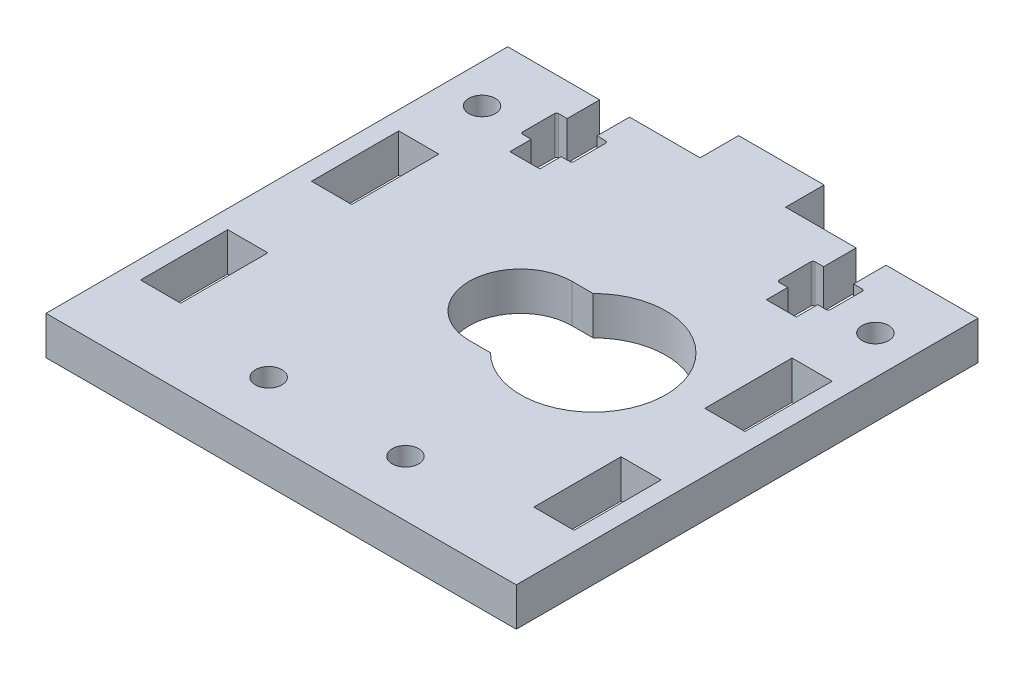
SolidWorks part; units mm, degrees
ref_plane "Front Plane" through (0, 0, 0) normal (0, 0, 1) x (1, 0, 0)
ref_plane "Top Plane" through (0, 0, 0) normal (0, 1, 0) x (1, 0, 0)
ref_plane "Right Plane" through (0, 0, 0) normal (1, 0, 0) x (0, 0, -1)
sketch "Sketch1" plane through (0, 0, 0) normal (0, 1, 0) x (1, 0, 0)
  line L1 (-27.5, 27) -> (27.5, 27)
  line L2 (-27.5, 27) -> (-27.5, -27)
  line L3 (-27.5, -27) -> (27.5, -27)
  line L4 (27.5, 27) -> (27.5, -27)
  line L5 (-27.5, 27) -> (27.5, -27) construction
  line L6 (-27.5, -27) -> (27.5, 27) construction
  point P0 (0, 0)
  dimension "D1" = 55
  dimension "D2" = 54
extrude "MainShape" add sketch "Sketch1" along normal blind 4.5
sketch "Sketch2" plane through (0, 4.5, 0) normal (0, 1, 0) x (1, 0, 0)
  line L0 (0, -27) -> (0, 27) construction
  line L1 (-27.5, -27) -> (27.5, -27) construction
  line L2 (27.5, 27) -> (-27.5, 27) construction
  line L4 (-5, 31.5) -> (5, 31.5)
  line L5 (-5, 31.5) -> (-5, 22.5)
  line L6 (-5, 22.5) -> (5, 22.5)
  line L7 (5, 31.5) -> (5, 22.5)
  line L8 (-5, 31.5) -> (5, 22.5) construction
  line L9 (-5, 22.5) -> (5, 31.5) construction
  dimension "D1" = 10
  dimension "D2" = 4.5
extrude "Tab1" add sketch "Sketch2" against normal through all
sketch "Sketch4" plane through (0, 4.5, 0) normal (0, 1, 0) x (1, 0, 0)
  line L0 (0, 31.5) -> (0, -27) construction
  line L1 (5, 31.5) -> (-5, 31.5) construction
  line L2 (-27.5, -27) -> (27.5, -27) construction
  line L3 (-15, 27) -> (-15, 16.5) construction
  line L4 (-5, 27) -> (-27.5, 27) construction
  line L5 (-13.25, 16.5) -> (-16.75, 16.5) construction
  line L6 (-16.75, 16.5) -> (-16.75, 27) construction
  line L7 (-13.25, 16.5) -> (-16.75, 16.5)
  line L8 (-16.75, 16.5) -> (-16.75, 19)
  line L9 (-16.75, 19) -> (-17.75, 19)
  line L10 (-18, 19.25) -> (-18, 22.95)
  line L11 (-17.75, 23.2) -> (-16.75, 23.2)
  line L12 (-16.75, 23.2) -> (-16.75, 27)
  line L13 (-16.75, 27) -> (-13.25, 27)
  line L14 (-13.25, 16.5) -> (-13.25, 27) construction
  line L15 (-13.25, 23.2) -> (-13.25, 27)
  line L16 (-12.25, 23.2) -> (-13.25, 23.2)
  line L17 (-12, 19.25) -> (-12, 22.95)
  line L18 (-13.25, 19) -> (-12.25, 19)
  line L19 (-13.25, 16.5) -> (-13.25, 19)
  line L20 (13.25, 16.5) -> (13.25, 27) construction
  line L21 (16.75, 16.5) -> (16.75, 27) construction
  line L22 (13.25, 16.5) -> (16.75, 16.5) construction
  line L23 (15, 27) -> (15, 16.5) construction
  line L24 (13.25, 16.5) -> (13.25, 19)
  line L25 (13.25, 19) -> (12.25, 19)
  line L26 (12, 19.25) -> (12, 22.95)
  line L27 (12.25, 23.2) -> (13.25, 23.2)
  line L28 (13.25, 23.2) -> (13.25, 27)
  line L29 (16.75, 27) -> (13.25, 27)
  line L30 (16.75, 23.2) -> (16.75, 27)
  line L31 (17.75, 23.2) -> (16.75, 23.2)
  line L32 (18, 19.25) -> (18, 22.95)
  line L33 (16.75, 19) -> (17.75, 19)
  line L34 (16.75, 16.5) -> (16.75, 19)
  line L35 (13.25, 16.5) -> (16.75, 16.5)
  arc A0 (-17.75, 19) -> (-18, 19.25) centre (-17.75, 19.25) cw
  arc A1 (-12, 19.25) -> (-12.25, 19) centre (-12.25, 19.25) cw
  arc A2 (-12.25, 23.2) -> (-12, 22.95) centre (-12.25, 22.95) cw
  arc A3 (-18, 22.95) -> (-17.75, 23.2) centre (-17.75, 22.95) cw
  arc A4 (18, 22.95) -> (17.75, 23.2) centre (17.75, 22.95) ccw
  arc A5 (12.25, 23.2) -> (12, 22.95) centre (12.25, 22.95) ccw
  arc A6 (12, 19.25) -> (12.25, 19) centre (12.25, 19.25) ccw
  arc A7 (17.75, 19) -> (18, 19.25) centre (17.75, 19.25) ccw
  point P24 (-18, 19)
  point P27 (-12, 19)
  point P30 (-12, 23.2)
  point P33 (-18, 23.2)
  point P56 (18, 23.2)
  point P57 (12, 23.2)
  point P58 (12, 19)
  point P59 (18, 19)
  dimension "D7" = 0.25
  dimension "D1" = 10.5
  dimension "D2" = 1.75
  dimension "D3" = 4.2
  dimension "D4" = 3
  dimension "D5" = 8
  dimension "D6" = 15
extrude "Cut-Extrude2" cut sketch "Sketch4" against normal through all
sketch "Sketch5" plane through (0, 4.5, 0) normal (0, 1, 0) x (1, 0, 0)
  line L0 (0, -27) -> (0, 31.5) construction
  line L1 (-27.5, -27) -> (27.5, -27) construction
  line L2 (5, 31.5) -> (-5, 31.5) construction
  line L3 (23, 27) -> (23, -27) construction
  line L4 (27.5, 27) -> (16.75, 27) construction
  line L5 (-23, 27) -> (-23, -27) construction
  line L6 (20.65, 12.1) -> (25.35, 12.1)
  line L7 (20.65, 12.1) -> (20.65, 1.9)
  line L8 (20.65, 1.9) -> (25.35, 1.9)
  line L9 (25.35, 12.1) -> (25.35, 1.9)
  line L10 (20.65, 12.1) -> (25.35, 1.9) construction
  line L11 (20.65, 1.9) -> (25.35, 12.1) construction
  line L12 (-20.65, 1.9) -> (-25.35, 12.1) construction
  line L13 (-20.65, 12.1) -> (-25.35, 1.9) construction
  line L14 (-25.35, 12.1) -> (-25.35, 1.9)
  line L15 (-20.65, 1.9) -> (-25.35, 1.9)
  line L16 (-20.65, 12.1) -> (-20.65, 1.9)
  line L17 (-20.65, 12.1) -> (-25.35, 12.1)
  line L18 (-27.5, -3) -> (27.5, -3) construction
  line L19 (-27.5, 27) -> (-27.5, -27) construction
  line L20 (27.5, -27) -> (27.5, 27) construction
  line L21 (-20.65, -18.1) -> (-25.35, -7.9) construction
  line L22 (-20.65, -7.9) -> (-25.35, -18.1) construction
  line L23 (20.65, -7.9) -> (25.35, -18.1) construction
  line L24 (20.65, -18.1) -> (25.35, -7.9) construction
  line L25 (-20.65, -18.1) -> (-25.35, -18.1)
  line L26 (-20.65, -18.1) -> (-20.65, -7.9)
  line L27 (-20.65, -7.9) -> (-25.35, -7.9)
  line L28 (-25.35, -18.1) -> (-25.35, -7.9)
  line L29 (25.35, -18.1) -> (25.35, -7.9)
  line L30 (20.65, -7.9) -> (25.35, -7.9)
  line L31 (20.65, -18.1) -> (20.65, -7.9)
  line L32 (20.65, -18.1) -> (25.35, -18.1)
  line L33 (-20.65, 12.1) -> (-25.35, 1.9) construction
  point P10 (23, 7)
  point P21 (-23, 7)
  point P36 (-23, -13)
  point P37 (23, -13)
  dimension "D1" = 23
  dimension "D2" = 10.2
  dimension "D3" = 4.7
  dimension "D4" = 20
  dimension "D5" = 20
extrude "Cut-Extrude3" cut sketch "Sketch5" against normal through all
sketch "Sketch6" plane through (0, 4.5, 0) normal (0, 1, 0) x (1, 0, 0)
  line L0 (0, -27) -> (0, 27) construction
  line L1 (5, 31.5) -> (-5, 31.5) construction
  line L3 (-27.5, 1) -> (27.5, 1) construction
  line L4 (-27.5, 27) -> (-27.5, -27) construction
  line L5 (27.5, -27) -> (27.5, 27) construction
  line L6 (27.5, 27) -> (16.75, 27) construction
  line L7 (-27.5, -27) -> (27.5, -27) construction
  line L9 (-27.5, 27) -> (27.5, 27) construction
  circle A0 centre (0, 1) radius 12
  point P4 (0, 31.5)
  dimension "D1" = 24
  dimension "D2" = 26
extrude "Cut-Extrude4" cut sketch "Sketch6" against normal through all
sketch "Sketch7" plane through (0, 4.5, 0) normal (0, 1, 0) x (1, 0, 0)
  line L0 (0, 1) -> (0, -27) construction
  line L3 (-27.5, -27) -> (27.5, -27) construction
  line L4 (8, -20.46) -> (-8, -20.46) construction
  circle A1 centre (-8, -20.46) radius 1.55
  circle A2 centre (8, -20.46) radius 1.55
  point P8 (0, -20.46)
  dimension "D1" = 3.1
  dimension "D2" = 8
  dimension "D3" = 21.46
extrude "Cut-Extrude5" [suppressed] cut sketch "Sketch7" against normal through all
sketch "Sketch8" plane through (0, 4.5, 0) normal (0, 1, 0) x (1, 0, 0)
  line L0 (-12, 1) -> (12, 1) construction
  line L1 (0, 1) -> (0, -20.46) construction
  line L2 (8, -20.46) -> (-8, -20.46) construction
  line L3 (0, -11) -> (0, 13) construction
  circle A0 centre (-8, -20.46) radius 1.55
  circle A1 centre (0, 1) radius 12 construction
  circle A2 centre (8, -20.46) radius 1.55
  dimension "D2" = 8
  dimension "D3" = 3.1
  dimension "D1" = 90
  dimension "D4" = 21.46
extrude "Cut-Extrude6" cut sketch "Sketch8" against normal through all
sketch "Sketch9" plane through (0, 4.5, 0) normal (0, 1, 0) x (1, 0, 0)
  line L0 (0, -27) -> (0, 31.5) construction
  line L1 (-27.5, -27) -> (27.5, -27) construction
  line L2 (5, 31.5) -> (-5, 31.5) construction
  line L3 (16, -27) -> (16, -16.5) construction
  line L4 (14.25, -16.5) -> (17.75, -16.5) construction
  line L5 (17.75, -16.5) -> (17.75, -27) construction
  line L6 (17.75, -27) -> (17.75, -23.2)
  line L7 (17.75, -23.2) -> (18.75, -23.2)
  line L8 (19, -22.95) -> (19, -19.25)
  line L9 (18.75, -19) -> (17.75, -19)
  line L10 (17.75, -19) -> (17.75, -16.5)
  line L11 (17.75, -16.5) -> (14.25, -16.5)
  line L12 (17.75, -27) -> (14.25, -27)
  line L13 (14.25, -16.5) -> (14.25, -27) construction
  line L14 (14.25, -19) -> (14.25, -16.5)
  line L15 (13.25, -19) -> (14.25, -19)
  line L16 (13, -22.95) -> (13, -19.25)
  line L17 (14.25, -23.2) -> (13.25, -23.2)
  line L18 (14.25, -27) -> (14.25, -23.2)
  line L19 (-14.25, -16.5) -> (-14.25, -27) construction
  line L20 (-17.75, -16.5) -> (-17.75, -27) construction
  line L21 (-14.25, -16.5) -> (-17.75, -16.5) construction
  line L22 (-16, -27) -> (-16, -16.5) construction
  line L23 (-14.25, -27) -> (-14.25, -23.2)
  line L24 (-14.25, -23.2) -> (-13.25, -23.2)
  line L25 (-13, -22.95) -> (-13, -19.25)
  line L26 (-13.25, -19) -> (-14.25, -19)
  line L27 (-14.25, -19) -> (-14.25, -16.5)
  line L28 (-17.75, -27) -> (-14.25, -27)
  line L29 (-17.75, -16.5) -> (-14.25, -16.5)
  line L30 (-17.75, -19) -> (-17.75, -16.5)
  line L31 (-18.75, -19) -> (-17.75, -19)
  line L32 (-19, -22.95) -> (-19, -19.25)
  line L33 (-17.75, -23.2) -> (-18.75, -23.2)
  line L34 (-17.75, -27) -> (-17.75, -23.2)
  arc A0 (18.75, -23.2) -> (19, -22.95) centre (18.75, -22.95) ccw
  arc A1 (19, -19.25) -> (18.75, -19) centre (18.75, -19.25) ccw
  arc A2 (13, -19.25) -> (13.25, -19) centre (13.25, -19.25) cw
  arc A3 (13.25, -23.2) -> (13, -22.95) centre (13.25, -22.95) cw
  arc A4 (-13.25, -23.2) -> (-13, -22.95) centre (-13.25, -22.95) ccw
  arc A5 (-13, -19.25) -> (-13.25, -19) centre (-13.25, -19.25) ccw
  arc A6 (-19, -19.25) -> (-18.75, -19) centre (-18.75, -19.25) cw
  arc A7 (-18.75, -23.2) -> (-19, -22.95) centre (-18.75, -22.95) cw
  point P16 (19, -23.2)
  point P19 (19, -19)
  point P30 (13, -19)
  point P31 (13, -23.2)
  point P54 (-13, -23.2)
  point P55 (-13, -19)
  point P56 (-19, -19)
  point P57 (-19, -23.2)
  dimension "D7" = 0.25
  dimension "D1" = 10.5
  dimension "D2" = 1.75
  dimension "D3" = 8
  dimension "D4" = 4.2
  dimension "D5" = 3
  dimension "D6" = 16
extrude "Cut-Extrude7" [suppressed] cut sketch "Sketch9" against normal through all
sketch "Sketch10" [suppressed] plane through (0, 0, 27) normal (0, 0, 1) x (1, 0, 0)
  line L0 (-27.5, 2.25) -> (27.5, 2.25) construction
  line L1 (-27.5, 4.5) -> (-27.5, 0) construction
  line L2 (27.5, 4.5) -> (27.5, 0) construction
  line L3 (-16, 4.5) -> (-16, 0) construction
  line L4 (-14.25, 4.5) -> (-17.75, 4.5) construction
  line L5 (16, 4.5) -> (16, 0) construction
  line L6 (17.75, 4.5) -> (14.25, 4.5) construction
  line L7 (17.75, 0) -> (14.25, 0) construction
  line L8 (-14.25, 0) -> (-17.75, 0) construction
  circle A0 centre (-16, 2.25) radius 1.6
  circle A1 centre (16, 2.25) radius 1.6
  dimension "D1" = 3.2
  dimension "D2" = 3.2
sketch "Sketch11" plane through (0, 4.5, 0) normal (0, 1, 0) x (1, 0, 0)
  line L0 (-20.65, 7) -> (-25.35, 7) construction
  line L1 (-20.65, 1.9) -> (-20.65, 12.1) construction
  line L2 (-25.35, 12.1) -> (-25.35, 1.9) construction
  line L3 (-23, 7) -> (-23, 27) construction
  line L4 (-16.75, 27) -> (-27.5, 27) construction
  line L5 (0, 31.5) -> (0, 0) construction
  line L6 (5, 31.5) -> (-5, 31.5) construction
  line L7 (23, 7) -> (23, 27) construction
  line L8 (20.65, 7) -> (25.35, 7) construction
  line L9 (-23, 7) -> (-23, 27) construction
  circle A0 centre (-23, 19.5) radius 1.55
  circle A1 centre (23, 19.5) radius 1.55
  dimension "D1" = 3.1
  dimension "D2" = 7.5
extrude "Cut-Extrude8" cut sketch "Sketch11" against normal through all
sketch "Sketch12" [suppressed] plane through (0, 4.5, 0) normal (0, 1, 0) x (1, 0, 0)
  line L0 (-27.5, -7) -> (-34, -17)
  line L1 (-27.5, 27) -> (-27.5, -27) construction
  line L2 (-34, -17) -> (-34, -27)
  line L3 (-34, -27) -> (-27.5, -27)
  line L4 (-27.5, -27) -> (-27.5, -7)
  line L5 (-27.5, -27) -> (27.5, -27) construction
  line L6 (0, -27) -> (0, 31.5) construction
  line L7 (5, 31.5) -> (-5, 31.5) construction
  line L8 (27.5, -27) -> (27.5, -7)
  line L9 (34, -27) -> (27.5, -27)
  line L10 (34, -17) -> (34, -27)
  line L11 (27.5, -7) -> (34, -17)
  point P4 (0, -27)
  dimension "D1" = 34
  dimension "D2" = 10
  dimension "D3" = 20
extrude "Boss-Extrude1" [suppressed] add sketch "Sketch12" against normal through all
sketch "Sketch14" [suppressed] plane through (0, 4.5, 0) normal (0, 1, 0) x (1, 0, 0)
  line L0 (-34, -27) -> (34, -27) construction
  line L2 (-34, -27) -> (34, -27) construction
  line L3 (0, -27) -> (0, 31.5) construction
  line L4 (5, 31.5) -> (-5, 31.5) construction
  line L6 (26.25, -16.5) -> (26.25, -27) construction
  line L8 (-28, -27) -> (-28, -16.5) construction
  line L9 (-26.25, -16.5) -> (-29.75, -16.5) construction
  line L10 (-29.75, -16.5) -> (-29.75, -27) construction
  line L11 (-26.25, -27) -> (-29.75, -27)
  line L12 (-29.75, -27) -> (-29.75, -23.2)
  line L13 (-29.75, -23.2) -> (-30.75, -23.2)
  line L14 (-31, -22.95) -> (-31, -19.25)
  line L15 (-30.75, -19) -> (-29.75, -19)
  line L16 (-29.75, -19) -> (-29.75, -16.5)
  line L17 (-29.75, -16.5) -> (-26.25, -16.5)
  line L18 (-26.25, -16.5) -> (-26.25, -27) construction
  line L19 (-26.25, -19) -> (-26.25, -16.5)
  line L20 (-25.25, -19) -> (-26.25, -19)
  line L21 (-25, -22.95) -> (-25, -19.25)
  line L22 (-26.25, -23.2) -> (-25.25, -23.2)
  line L23 (-26.25, -27) -> (-26.25, -23.2)
  line L24 (29.75, -16.5) -> (29.75, -27) construction
  line L25 (26.25, -16.5) -> (29.75, -16.5) construction
  line L26 (28, -27) -> (28, -16.5) construction
  line L27 (26.25, -27) -> (26.25, -23.2)
  line L28 (26.25, -23.2) -> (25.25, -23.2)
  line L29 (25, -22.95) -> (25, -19.25)
  line L30 (25.25, -19) -> (26.25, -19)
  line L31 (26.25, -19) -> (26.25, -16.5)
  line L32 (29.75, -16.5) -> (26.25, -16.5)
  line L33 (29.75, -19) -> (29.75, -16.5)
  line L34 (30.75, -19) -> (29.75, -19)
  line L35 (31, -22.95) -> (31, -19.25)
  line L36 (29.75, -23.2) -> (30.75, -23.2)
  line L37 (29.75, -27) -> (29.75, -23.2)
  line L38 (26.25, -27) -> (29.75, -27)
  line L39 (-26.25, -16.5) -> (-26.25, -27) construction
  arc A0 (-30.75, -23.2) -> (-31, -22.95) centre (-30.75, -22.95) cw
  arc A1 (-31, -19.25) -> (-30.75, -19) centre (-30.75, -19.25) cw
  arc A2 (-25, -19.25) -> (-25.25, -19) centre (-25.25, -19.25) ccw
  arc A3 (-25.25, -23.2) -> (-25, -22.95) centre (-25.25, -22.95) ccw
  arc A4 (25.25, -23.2) -> (25, -22.95) centre (25.25, -22.95) cw
  arc A5 (25, -19.25) -> (25.25, -19) centre (25.25, -19.25) cw
  arc A6 (31, -19.25) -> (30.75, -19) centre (30.75, -19.25) ccw
  arc A7 (30.75, -23.2) -> (31, -22.95) centre (30.75, -22.95) ccw
  point P2 (0, -27)
  dimension "D10" = 0.25
  dimension "D4" = 1.75
  dimension "D6" = 10.5
  dimension "D2" = 28
  dimension "D3" = 3
  dimension "D5" = 4.2
  dimension "D7" = 8
extrude "Cut-Extrude9" [suppressed] cut sketch "Sketch14" against normal through all
sketch "Sketch15" plane through (0, 4.5, 0) normal (0, 1, 0) x (1, 0, 0)
  circle A0 centre (0, 1) radius 12
  circle A1 centre (0, 1) radius 6
  circle A2 centre (0, 1) radius 12 construction
  dimension "D1" = 12
extrude "Boss-Extrude2" add sketch "Sketch15" against normal through all
sketch "Sketch16" plane through (0, 4.5, 0) normal (0, 1, 0) x (1, 0, 0)
  line L0 (0, 1) -> (27.5, 1) construction
  line L1 (27.5, -27) -> (27.5, 27) construction
  line L2 (0, 7) -> (2.4792, 7)
  line L3 (0, -5) -> (2.4792, -5)
  line L4 (0, 7) -> (0, -5)
  arc A0 (2.4792, -5) -> (2.4792, 7) centre (8.5, 1) ccw
  circle A1 centre (0, 1) radius 6 construction
  dimension "D1" = 17
  dimension "D2" = 8.5
extrude "Cut-Extrude10" cut sketch "Sketch16" against normal through all
equation "\"X-ROD-SPACING\"=45"
equation "\"Y-ROD-SPACING\"=75"
equation "\"Z-ROD-SPACING\"=17.5"
equation "\"Y-BED-OFFSET\"=2"
equation "\"Y-BED-ROD-INSET\"=3.5"
equation "\"Y-BED-SCREW-SPACING\"=209"
equation "\"Y-BED-SCREW-CUTOUT-SLOT-HEIGHT\"=2"
equation "\"T-SLOT-NUT-FILLET-RADIUS\"=0.25"
equation "\"T-SLOT-SCREW-SHAFT-RADIUS\"=1.75"
equation "\"T-SLOT-SCREW-SHAFT-CUTOUT-LENGTH\"=10.5"
equation "\"T-SLOT-NUT-DEPTH\"=4.2"
equation "\"T-SLOT-NUT-WIDTH\"=3"
equation "\"T-SLOT-NUT-END-DISTANCE\"=8"
equation "\"ACRYLIC-THICKNESS\"=10"
equation "\"ACRYLIC-THICKNESS2\"=4.5"
equation "\"ACRYLIC-TAB-CUTOUT-SIZE\"=\"ACRYLIC-THICKNESS\"+\"ACRYLIC-TAB-TOLERANCE\"*2"
equation "\"ACRYLIC-TAB-WIDTH\"=\"ACRYLIC-THICKNESS\""
equation "\"ACRYLIC-M3-HOLE\"=3.1"
equation "\"SMOOTHROD-CAP-SCREW-DISTANCE\"=20"
equation "\"FRAME-WIDTH-INNER\"=370"
equation "\"NEMA17-HOLE-SPACING\"=31"
equation "\"NEMA17-CENTRAL-CUTOUT\"=22.5"
equation "\"Z-BRACKET-REACH\"=55"
equation "\"Z-ROD-INSET\"=16"
equation "\"TOP-BRACKET-SPACING\"=40"
equation "\"SMOOTHROD-X-LENGTH\"=350"
equation "\"SMOOTHROD-Y-LENGTH\"=350"
equation "\"SMOOTHROD-Z-LENGTH\"=350"
equation "\"SMOOTHROD-TIGHTENING-HEADROOM\"=.25"
equation "\"LEADSCREW-Z-LENGTH\"=300"
equation "\"SCREW-LENGTH-FRAME\"=\"ACRYLIC-THICKNESS\" + 10"
equation "\"SCREW-LENGTH-MOTOR\"=\"ACRYLIC-THICKNESS\" + 5"
equation "\"SCREW-LENGTH-EXTRUDER\"=28"
equation "\"SCREW-HEAD-RADIUS\"=6"
equation "\"PRINTED-X-SMOOTHROD-DIAMETER\"=8.2"
equation "\"PRINTED-X-SMOOTHROD-CUTOUT\"=10"
equation "\"PRINTED-X-BASE-HEIGHT\"=10"
equation "\"PRINTED-LM8UU-CUTOUT-SIZE\"=15.25"
equation "\"PRINTED-LM8UU-CUTOUT-LENGTH\"=24.5"
equation "\"PRINTED-X-IDLER-HEIGHT\"=16"
equation "\"PSU-MOUNTING-WIDTH\"=95"
equation "\"PSU-MOUNTING-HEIGHT\"=177"
equation "\"Y-BELT-TO-ROD-DISTANCE\"=20"
equation "\"SPOOL-HOLDER-ROD-SPACING\"=150"
equation "\"ACRYLIC-X-CARRIAGE-WIDTH\"=55"
equation "\"ACRYLIC-X-CARRIAGE-HEIGHT\"=75"
equation "\"ACRYLIC-X-CARRIAGE-SCREW-SPACING-X\"=15"
equation "\"ACRYLIC-X-CARRIAGE-SCREW-SPACING-Y\"=33"
equation "\"ACRYLIC-X-CARRIAGE-CENTER-TAB-SPACING\"=14"
equation "\"D1@Sketch1\"=\"ACRYLIC-X-CARRIAGE-WIDTH\""
equation "\"D1@MainShape\" = \"ACRYLIC-THICKNESS2\""
equation "\"D1@Sketch2\"=\"ACRYLIC-TAB-WIDTH\""
equation "\"D2@Sketch2\"=\"ACRYLIC-THICKNESS2\""
equation "\"D1@Sketch4\"=\"T-SLOT-SCREW-SHAFT-CUTOUT-LENGTH\""
equation "\"D2@Sketch4\"=\"T-SLOT-SCREW-SHAFT-RADIUS\""
equation "\"D3@Sketch4\"=\"T-SLOT-NUT-DEPTH\""
equation "\"D4@Sketch4\"=\"T-SLOT-NUT-WIDTH\""
equation "\"D5@Sketch4\"=\"T-SLOT-NUT-END-DISTANCE\""
equation "\"D6@Sketch4\"=\"ACRYLIC-X-CARRIAGE-SCREW-SPACING-X\""
equation "\"D7@Sketch4\"=\"T-SLOT-NUT-FILLET-RADIUS\""
equation "\"ACRYLIC-X-CARRIAGE-EXTRUDER-SHELF-DEPTH\"=\"ACRYLIC-X-CARRIAGE-EXTRUDER-OFFSET\" + 28"
equation "\"D2@Sketch1\"=\"ACRYLIC-X-CARRIAGE-EXTRUDER-SHELF-DEPTH\""
equation "\"ACRYLIC-X-CARRIAGE-LM8UU-CUTOUT-WIDTH\"=24.25"
equation "\"ACRYLIC-X-CARRIAGE-EXTRUDER-BRACE-SPACING\"=23"
equation "\"ACRYLIC-X-CARRIAGE-EXTRUDER-BRACE-TAB-OFFSET\"=20"
equation "\"ACRYLIC-X-CARRIAGE-EXTRUDER-BRACE-HEIGHT\"=35"
equation "\"ACRYLIC-X-CARRIAGE-EXTRUDER-BRACE-SCREW-SPACING\"=22"
equation "\"D1@Sketch5\"=\"ACRYLIC-X-CARRIAGE-EXTRUDER-BRACE-SPACING\""
equation "\"D2@Sketch5\"=\"ACRYLIC-TAB-CUTOUT-SIZE\""
equation "\"D3@Sketch5\"=\"ACRYLIC-THICKNESS2\"+\"ACRYLIC-TAB-TOLERANCE\"*2"
equation "\"D4@Sketch5\"=\"ACRYLIC-X-CARRIAGE-EXTRUDER-BRACE-TAB-OFFSET\""
equation "\"D1@Sketch7\"=\"ACRYLIC-M3-HOLE\""
equation "\"D3@Sketch8\"=\"ACRYLIC-M3-HOLE\""
equation "\"ACRYLIC-X-CARRIAGE-EXTRUDER-ANGLE\"=90"
equation "\"D1@Sketch8\"=\"ACRYLIC-X-CARRIAGE-EXTRUDER-ANGLE\""
equation "\"ACRYLIC-X-CARRIAGE-EXTRUDER-OFFSET\"=26"
equation "\"D2@Sketch6\"=\"ACRYLIC-X-CARRIAGE-EXTRUDER-OFFSET\""
equation "\"D1@Sketch9\"=\"T-SLOT-SCREW-SHAFT-CUTOUT-LENGTH\""
equation "\"D2@Sketch9\"=\"T-SLOT-SCREW-SHAFT-RADIUS\""
equation "\"D3@Sketch9\"=\"T-SLOT-NUT-END-DISTANCE\""
equation "\"D4@Sketch9\"=\"T-SLOT-NUT-DEPTH\""
equation "\"D5@Sketch9\"=\"T-SLOT-NUT-WIDTH\""
equation "\"D7@Sketch9\"=\"T-SLOT-NUT-FILLET-RADIUS\""
equation "\"ACRYLIC-TAB-TOLERANCE\"=.1"
equation "\"D1@Sketch11\"=\"ACRYLIC-M3-HOLE\""
equation "\"D6@Sketch14\"=\"T-SLOT-SCREW-SHAFT-CUTOUT-LENGTH\""
equation "\"D3@Sketch14\"=\"T-SLOT-NUT-WIDTH\""
equation "\"D5@Sketch14\"=\"T-SLOT-NUT-DEPTH\""
equation "\"D4@Sketch14\"=\"T-SLOT-SCREW-SHAFT-RADIUS\""
equation "\"D10@Sketch14\"=\"T-SLOT-NUT-FILLET-RADIUS\""
equation "\"D7@Sketch14\"=\"T-SLOT-NUT-END-DISTANCE\""
